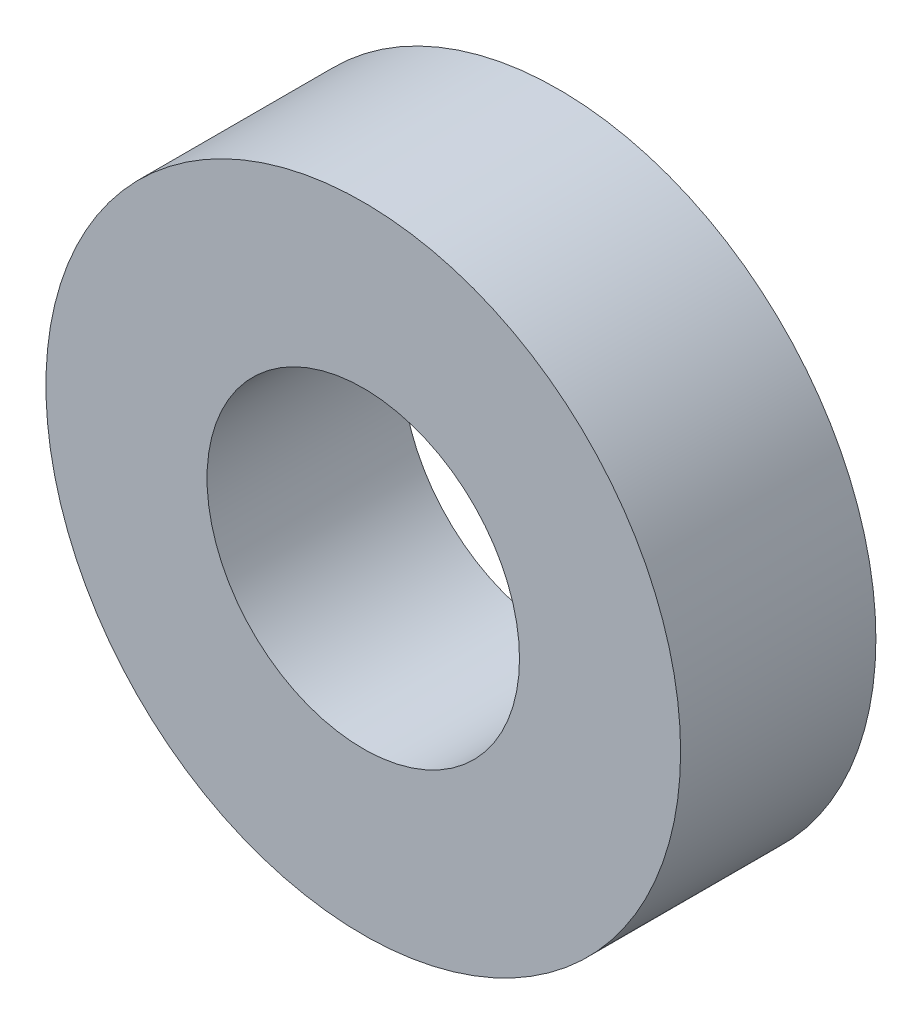
SolidWorks part; units mm, degrees
ref_plane "前视基准面" through (0, 0, 0) normal (0, 0, 1) x (1, 0, 0)
ref_plane "上视基准面" through (0, 0, 0) normal (0, 1, 0) x (1, 0, 0)
ref_plane "右视基准面" through (0, 0, 0) normal (1, 0, 0) x (0, 0, -1)
other "Configuration Table"
sketch "草图1" plane through (0, 0, 0) normal (0, 0, 1) x (1, 0, 0)
  circle A0 centre (0, 0) radius 6.5
  circle A1 centre (0, 0) radius 3.2
extrude "凸台-拉伸1" add sketch "草图1" along normal blind 4 flip side to cut
